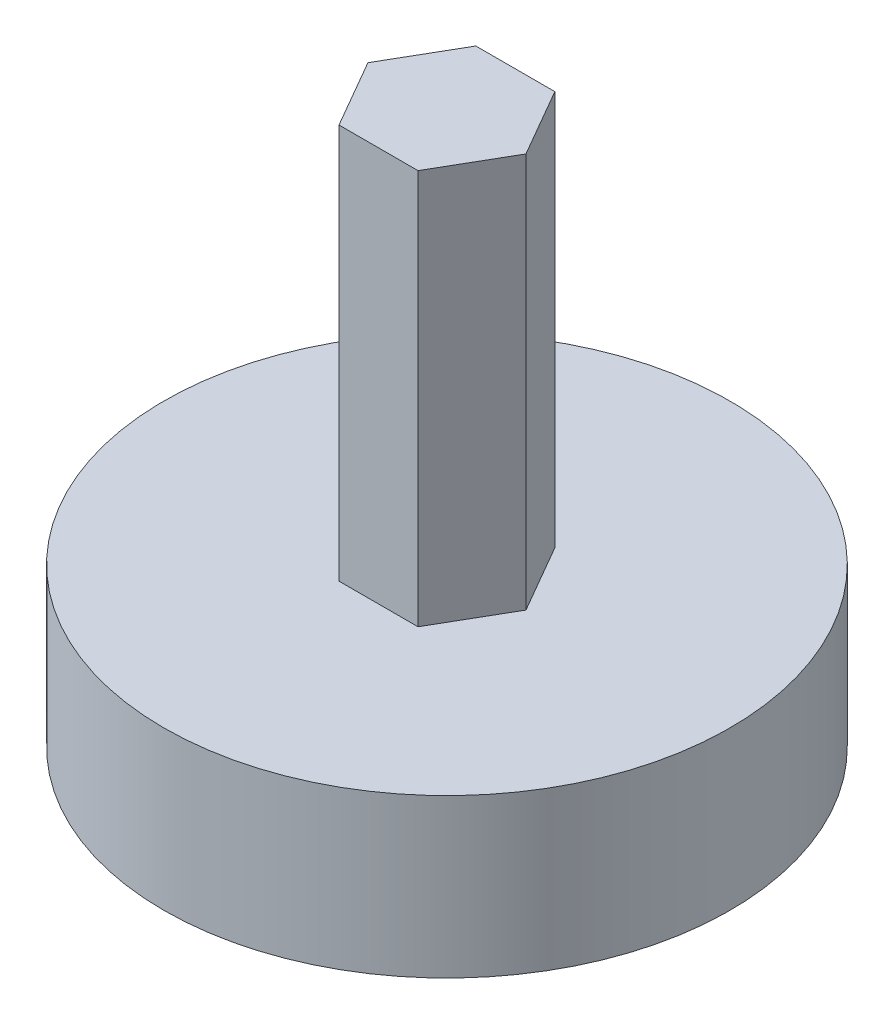
SolidWorks part; units mm, degrees
ref_plane "Front Plane" through (0, 0, 0) normal (0, 0, 1) x (1, 0, 0)
ref_plane "Top Plane" through (0, 0, 0) normal (0, 1, 0) x (1, 0, 0)
ref_plane "Right Plane" through (0, 0, 0) normal (1, 0, 0) x (0, 0, -1)
sketch "Sketch1" plane through (0, 0, 0) normal (0, 1, 0) x (1, 0, 0)
  circle A0 centre (0, 0) radius 10.75
  dimension "D1" = 21.5
extrude "Boss-Extrude1" add sketch "Sketch1" along normal blind 6
sketch "Sketch2" plane through (0, 6, 0) normal (0, 1, 0) x (1, 0, 0)
  line L1 (3, 0) -> (1.5, 2.5981)
  line L2 (1.5, 2.5981) -> (-1.5, 2.5981)
  line L3 (-1.5, 2.5981) -> (-3, 0)
  line L4 (-3, 0) -> (-1.5, -2.5981)
  line L5 (-1.5, -2.5981) -> (1.5, -2.5981)
  line L6 (1.5, -2.5981) -> (3, 0)
  circle A0 centre (0, 0) radius 2.5981 construction
  point P1 (3, 0)
  point P10 (3, 0)
  point P11 (0, 0)
  dimension "D1" = 3
extrude "Boss-Extrude2" add sketch "Sketch2" along normal blind 15
